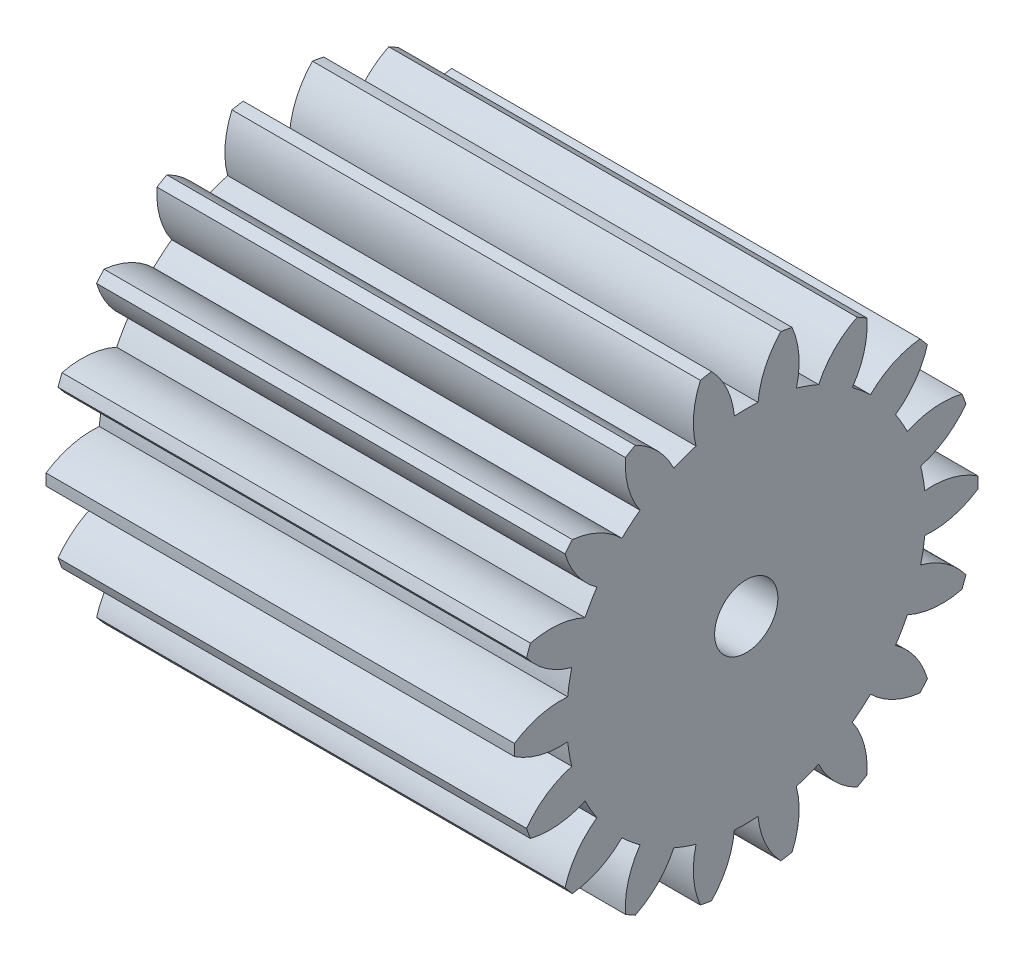
SolidWorks part; units mm, degrees
ref_plane "Plane1" through (0, 0, 0) normal (0, 0, 1) x (1, 0, 0)
ref_plane "Plane2" through (0, 0, 0) normal (0, 1, 0) x (1, 0, 0)
ref_plane "Plane3" through (0, 0, 0) normal (1, 0, 0) x (0, 0, -1)
other "Configuration Table"
sketch "HoldingSke" plane through (0, 0, 0) normal (0, 1, 0) x (1, 0, 0)
  line L0 (0, 0) -> (0.8646, -0.2809)
  line L1 (-15, 0) -> (100, 0) construction
  line L2 (0, 0) -> (-2.1039, 2.3779)
  line L3 (0, 0) -> (-11.863, 4.5341)
  line L4 (0, 0) -> (8.2133, 2.6687)
  line L5 (0, 0) -> (-46.8476, -17.4728)
  line L6 (0, 0) -> (-18.4278, -12.4333)
  line L7 (-2.1039, 2.3779) -> (8.6586, 51.206)
  line L8 (-76.2, 54.61) -> (-75.7, 54.61)
  line L9 (-71.009, 38.7566) -> (-53.1078, 45.2721)
  line L10 (-76.2, 71.12) -> (104.1128, 71.12)
  line L11 (0, 0) -> (-22.23, 0)
  line L12 (-76.2, 101.6) -> (-76.158, 101.6)
  line L13 (24.9733, 27.94) -> (52.9518, 28.4284)
  line L14 (24.9733, 27.94) -> (24.9743, 27.94)
  line L15 (24.9733, 27.94) -> (100.4006, 29.5858)
  line L16 (-63.627, -1.1) -> (-12.827, -1.1)
  circle A0 centre (0, 0) radius 1.5
  circle A1 centre (0, 0) radius 8.524
  circle A2 centre (0, 0) radius 37.5
  circle A3 centre (0, 0) radius 1.5
  dimension "MHD" = 17.048
  dimension "Hub_dia" = 75
  dimension "Bore" = 3
  dimension "MBD" = 3
  dimension "Num_teeth" = 18
  dimension "Pitch" = 0.9091
  dimension "Overall_len" = 50
  dimension "Show_teeth" = 18
  dimension "Thickness" = 22.23
  dimension "OAL" = 50.0002
  dimension "T_dim" = 0.5
  dimension "Ap" = 20
  dimension "H" = 19.05
  dimension "Pitch_radius" = 180.3128
  dimension "Width" = 22.23
  dimension "Backlash" = 0.042
  dimension "Addendum_fac" = 1
  dimension "Dedendum_fac" = 1.25
  dimension "Clearance_fac" = 0.25
  dimension "Dedendum_add" = 0.001
  dimension "Module" = 1.1
sketch "BasProSke" plane through (0, 0, 0) normal (0, 1, 0) x (1, 0, 0)
  line L0 (-10, 0) -> (60, 0) construction
  line L1 (0, 0) -> (0, 11)
  line L2 (0, 0) -> (22.23, 0)
  line L3 (22.23, 0) -> (22.23, 11)
  line L4 (22.23, 11) -> (0, 11)
  dimension "Thickness" = 22.23
  dimension "Diameter" = 22
revolve "Base-Revolve" add sketch "BasProSke" angle 360 about L0
sketch "TooCutSke" plane through (0, 0, 0) normal (1, 0, 0) x (0, 0, -1)
  line L1 (0, 0) -> (0, 107) construction
  line L2 (0, 0) -> (-0.9363, 9.8556) construction
  line L3 (0, 0) -> (-3.4273, 19.4371) construction
  line L4 (-0.9363, 9.8556) -> (-1.7136, 9.7186) construction
  arc A0 (0.562, 8.5055) -> (-0.562, 8.5055) centre (0, 0) ccw
  arc A1 (1.6649, 10.899) -> (-1.6649, 10.899) centre (0, 0) ccw
  circle A2 centre (0, 0) radius 9.9 construction
  circle A3 centre (0, 0) radius 9.303 construction
  arc A4 (-0.562, 8.5055) -> (-1.6649, 10.899) centre (-4.5051, 8.1394) ccw
  arc A5 (1.6649, 10.899) -> (0.562, 8.5055) centre (4.5051, 8.1394) ccw
  dimension "Root_dia" = 17.048
  dimension "Overcut_dia" = 22.0508
  dimension "Pitch_dia" = 19.8
  dimension "Base_dia" = 18.6059
  dimension "Flank_rad" = 3.96
  dimension "Half_ang" = 10
  dimension "Half_CT" = 0.7893
extrude "ToothCut" cut sketch "TooCutSke" along normal through all
fillet "Breaks" [suppressed] radius 0.022
fillet "RootFillets" [suppressed] radius 0.276
pattern_circular "TeethCuts" count 18 every 20 about axis through (-10, 0, 0) along (1, 0, 0) of "ToothCut", "RootFillets", "Breaks"
sketch "HubNeaOneSke" plane through (0, 0, 0) normal (-1, 0, 0) x (0, 0, 1)
  circle A0 centre (0, 0) radius 8.524
  dimension "Diameter" = 17.048
extrude "HubNearOne" [suppressed] add sketch "HubNeaOneSke" along normal blind 27.7702
sketch "HubNeaBotSke" plane through (0, 0, 0) normal (-1, 0, 0) x (0, 0, 1)
  circle A0 centre (0, 0) radius 8.524
  dimension "Diameter" = 17.048
extrude "HubNearBoth" [suppressed] add sketch "HubNeaBotSke" along normal blind 13.8851
ref_plane "FarPln" through (22.23, 0, 0) normal (1, 0, 0) x (0, 0, -1)
sketch "HubFarSke" plane through (22.23, 0, 0) normal (1, 0, 0) x (0, 0, -1)
  circle A0 centre (0, 0) radius 8.524
  dimension "Diameter" = 17.048
extrude "HubFar" [suppressed] add sketch "HubFarSke" along normal blind 13.8851
sketch "BorSke" plane through (0, 0, 0) normal (1, 0, 0) x (0, 0, -1)
  circle A0 centre (0, 0) radius 1.5
  dimension "Diameter" = 3
extrude "Bore" cut sketch "BorSke" along normal mid plane 100.0003
sketch "KeySke" plane through (0, 0, 0) normal (1, 0, 0) x (0, 0, -1)
  line L0 (-0.6, 0) -> (-0.6, 2)
  line L1 (-0.6, 2) -> (0.6, 2)
  line L2 (0.6, 2) -> (0.6, 0)
  line L3 (0, 0) -> (0, 34) construction
  line L4 (-0.6, 0) -> (0.6, 0)
  dimension "Offset" = 2
  dimension "Width" = 1.2
extrude "Keyway" [suppressed] cut sketch "KeySke" along normal mid plane 100.0003
pattern_circular "Keyway2" [suppressed] count 2 every 90 about axis through (-10, 0, 0) along (1, 0, 0)
equation "' \"Module@HoldingSke\" = 6.35"
equation "' \"Num_teeth@HoldingSke\" = 12"
equation "' \"Ap@HoldingSke\" =  20"
equation "' \"Ap@HoldingSke\" = 20"
equation "' \"Width@HoldingSke\" = 0.5 * 25.4"
equation "' \"Hub_dia@HoldingSke\"= 1 * 25.4"
equation "' \"Hub_dia@HoldingSke\" = 1 * 25.4"
equation "' \"Overall_len@HoldingSke\" = 1.0 * 25.4"
equation "' \"Bore@HoldingSke\" = 0.75 * 25.4"
equation "' \"T_dim@HoldingSke\" = 0.1 * 25.4"
equation "' \"Width@KeySke\" = 0.25 * 25.4"
equation "' \"Show_teeth@HoldingSke\" = 13"
equation "' \"Backlash@HoldingSke\" = 0.009 * 25.4"
equation "' \"Addendum_fac@HoldingSke\" = 1.0"
equation "' \"Dedendum_fac@HoldingSke\" = 1.25"
equation "' \"Dedendum_add@HoldingSke\" = 0.00005 * 25.4"
equation "' \"Clearance_fac@HoldingSke\" = 0.25"
equation "\"Pitch@HoldingSke\" = 1 / \"Module@HoldingSke\""
equation "\"Overcut_dia@TooCutSke\" = (\"Num_teeth@HoldingSke\" + 2 * \"Addendum_fac@HoldingSke\") / \"Pitch@HoldingSke\" + 0.002 * 25.4"
equation "\"Pitch_dia@TooCutSke\" = \"Num_teeth@HoldingSke\" / \"Pitch@HoldingSke\""
equation "\"Base_dia@TooCutSke\" = \"Num_teeth@HoldingSke\" / \"Pitch@HoldingSke\" * cos((\"Ap@HoldingSke\"  * 3.14159265 / 180))"
equation "\"Root_dia@TooCutSke\" = (\"Num_teeth@HoldingSke\" + 2) / \"Pitch@HoldingSke\" - 2 * (\"Addendum_fac@HoldingSke\" + \"Dedendum_fac@HoldingSke\") / \"Pitch@HoldingSke\" - \"Dedendum_add@HoldingSke\" * 2"
equation "\"Half_ang@TooCutSke\" = 180 / \"Num_teeth@HoldingSke\""
equation "\"Half_CT@TooCutSke\" = \"Num_teeth@HoldingSke\" / \"Pitch@HoldingSke\" * sin((3.14159265 / 2 / \"Num_teeth@HoldingSke\")) / 2 - 7 * \"Backlash@HoldingSke\" / 4"
equation "\"Flank_rad@TooCutSke\" = \"Num_teeth@HoldingSke\" / \"Pitch@HoldingSke\" / 5"
equation "\"Radius@RootFillets\" = \"Clearance_fac@HoldingSke\" / \"Pitch@HoldingSke\" + \"Dedendum_add@HoldingSke\""
equation "\"Break_rad@Breaks\" = 0.02 / \"Pitch@HoldingSke\""
equation "\"Thickness@HoldingSke\" = \"Width@HoldingSke\""
equation "\"OAL@HoldingSke\" = \"Thickness@HoldingSke\""
equation "\"MHD@HoldingSke\" = (\"Num_teeth@HoldingSke\" + 2) / \"Pitch@HoldingSke\" - 2 * (\"Addendum_fac@HoldingSke\" + \"Dedendum_fac@HoldingSke\")  / \"Pitch@HoldingSke\" - \"Dedendum_add@HoldingSke\" * 2"
equation "\"MBD@HoldingSke\" = (\"Num_teeth@HoldingSke\" + 2) / \"Pitch@HoldingSke\" - 2 * (\"Addendum_fac@HoldingSke\" + \"Dedendum_fac@HoldingSke\")  / \"Pitch@HoldingSke\" - \"Dedendum_add@HoldingSke\" * 2 - 0.002 * 25.4"
equation "\"MHD@HoldingSke\" = ((sgn( \"MHD@HoldingSke\" - \"Hub_dia@HoldingSke\" )-1)*( \"MHD@HoldingSke\" - \"Hub_dia@HoldingSke\" ))/-2+ \"Hub_dia@HoldingSke\""
equation "\"MBD@HoldingSke\" = ((sgn( \"MBD@HoldingSke\" - \"Bore@HoldingSke\" )-1)*( \"MBD@HoldingSke\" - \"Bore@HoldingSke\" ))/-2+ \"Bore@HoldingSke\""
equation "\"OAL@HoldingSke\" = ((sgn( \"OAL@HoldingSke\" - \"Overall_len@HoldingSke\" )+1)*( \"OAL@HoldingSke\" - \"Overall_len@HoldingSke\" ))/2 + \"Overall_len@HoldingSke\" + 0.000002 * 25.4"
equation "\"Num_teeth@TeethCuts\" = int( \"Show_teeth@HoldingSke\" ) + 1"
equation "\"Num_teeth@TeethCuts\" = ((sgn( \"Num_teeth@TeethCuts\" - \"Num_teeth@HoldingSke\" )-1)*( \"Num_teeth@TeethCuts\" - \"Num_teeth@HoldingSke\" ))/-2+ \"Num_teeth@HoldingSke\""
equation "\"Num_teeth@TeethCuts\" = ((sgn( \"Num_teeth@TeethCuts\" - 2.0)+1)*( \"Num_teeth@TeethCuts\" - 2.0))/2 +2.0"
equation "\"Angle@TeethCuts\" = 360.0 / \"Num_teeth@HoldingSke\""
equation "\"Diameter@BasProSke\" = (\"Num_teeth@HoldingSke\" + 2 * \"Addendum_fac@HoldingSke\") / \"Pitch@HoldingSke\""
equation "\"Thickness@BasProSke\"  = \"Thickness@HoldingSke\""
equation "' \"Fillet_rad@BasProSke\" =  \"Thickness@HoldingSke\" * 0.05"
equation "' \"Fillet_rad@BasProSke\" = \"Thickness@HoldingSke\" * 0.05"
equation "\"MHD@HoldingSke\" = ((sgn( \"MHD@HoldingSke\" - \"Root_dia@TooCutSke\" )-1)*( \"MHD@HoldingSke\" - \"Root_dia@TooCutSke\" ))/-2+ \"Root_dia@TooCutSke\""
equation "\"Diameter@HubNeaOneSke\" = \"MHD@HoldingSke\""
equation "\"Length@HubNearOne\" = \"OAL@HoldingSke\" - \"Thickness@BasProSke\""
equation "\"Diameter@HubNeaBotSke\" = \"MHD@HoldingSke\""
equation "\"Length@HubNearBoth\" = ( \"OAL@HoldingSke\" - \"Thickness@BasProSke\" ) / 2.0"
equation "\"Thickness@FarPln\" = \"Thickness@BasProSke\""
equation "\"Diameter@HubFarSke\" = \"MHD@HoldingSke\""
equation "\"Length@HubFar\" = ( \"OAL@HoldingSke\" - \"Thickness@BasProSke\" ) / 2.0"
equation "\"Diameter@BorSke\" = \"MBD@HoldingSke\""
equation "\"D1@Bore\" = \"OAL@HoldingSke\" * 2.0"
equation "\"D1@Keyway\" = \"OAL@HoldingSke\" * 2.0"
equation "\"Offset@KeySke\" = \"T_dim@HoldingSke\" + \"MBD@HoldingSke\" / 2.0"
